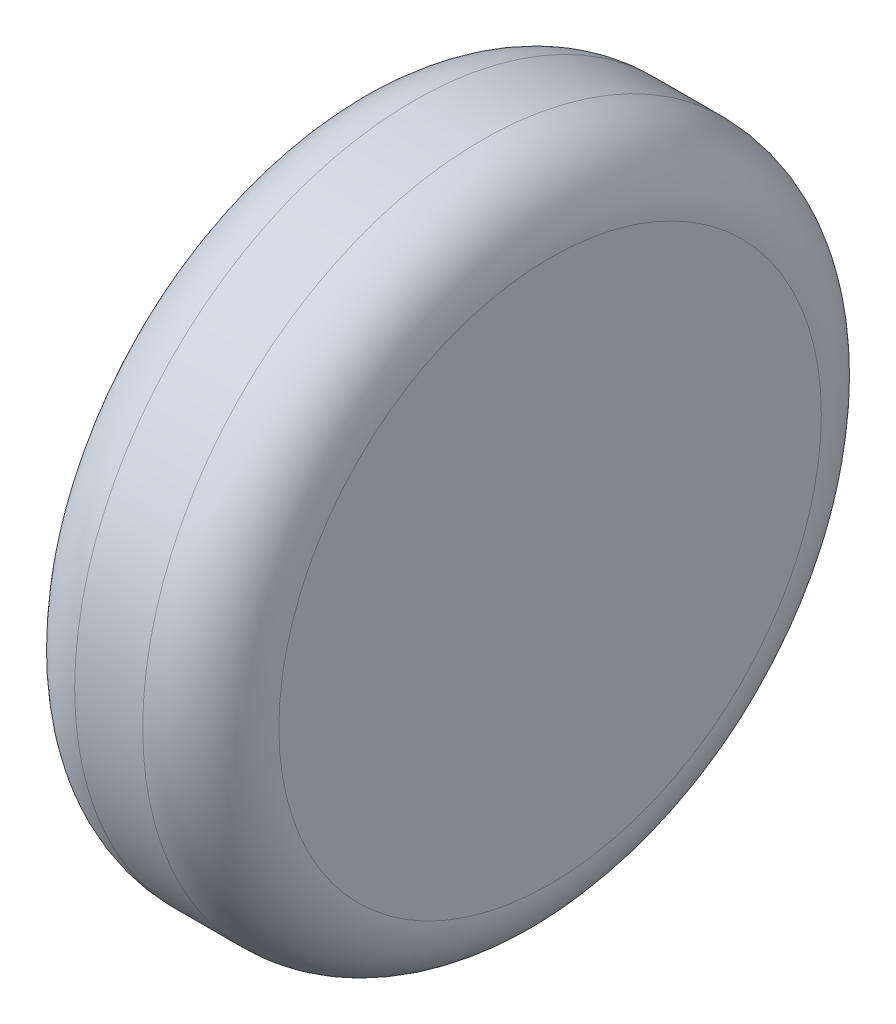
SolidWorks part; units mm, degrees
ref_plane "Front Plane" through (0, 0, 0) normal (0, 0, 1) x (1, 0, 0)
ref_plane "Top Plane" through (0, 0, 0) normal (0, 1, 0) x (1, 0, 0)
ref_plane "Right Plane" through (0, 0, 0) normal (1, 0, 0) x (0, 0, -1)
sketch "Sketch1" plane through (0, 0, 0) normal (1, 0, 0) x (0, 0, -1)
  circle A0 centre (0, 0) radius 63.2968
  dimension "D1" = 126.5936
extrude "Boss-Extrude1" add sketch "Sketch1" along normal blind 38.1
fillet "Fillet1" radius 12.7 2 edges at (38.1, 0, -63.2968) (0, 0, -63.2968)
